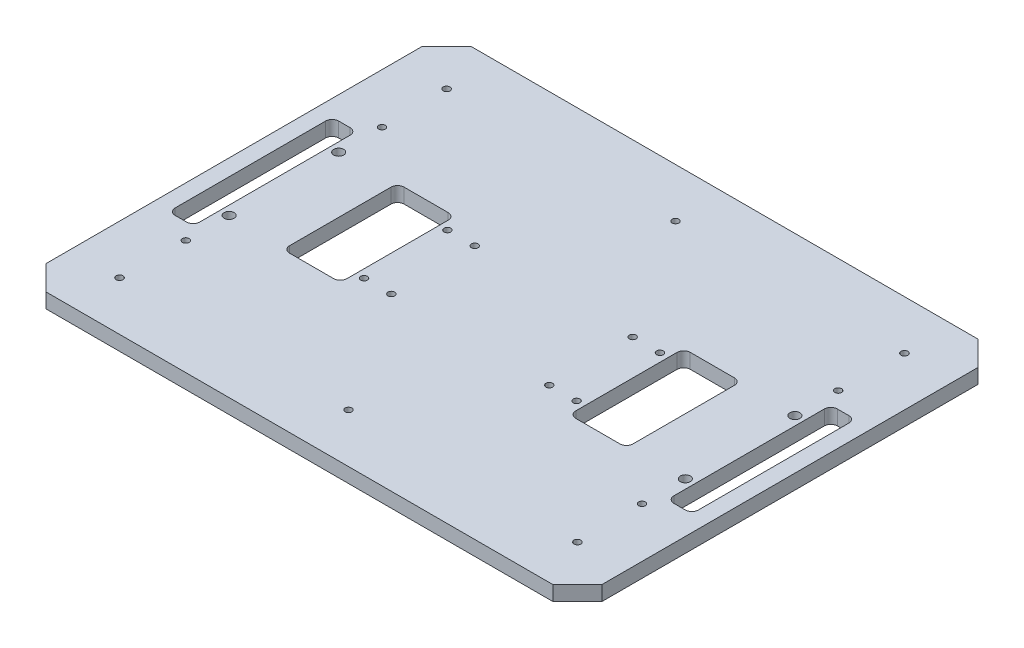
SolidWorks part; units mm, degrees
ref_plane "Plan de face" through (0, 0, 0) normal (0, 0, 1) x (1, 0, 0)
ref_plane "Plan de dessus" through (0, 0, 0) normal (0, 1, 0) x (1, 0, 0)
ref_plane "Plan de droite" through (0, 0, 0) normal (1, 0, 0) x (0, 0, -1)
sketch "Esquisse3" plane through (0, 0, 0) normal (0, 1, 0) x (1, 0, 0)
  line L0 (-281.7629, 0) -> (308.2067, 0) construction
  line L1 (0, 156.6109) -> (0, -136.5502) construction
  line L2 (155, 130) -> (-155, 130)
  line L3 (-170, 115) -> (-170, -115)
  line L4 (-160, -46) -> (-160, 46)
  line L5 (-156, 50) -> (-149, 50)
  line L6 (-145, 46) -> (-145, -46)
  line L7 (-105, 0) -> (-105, 31)
  line L8 (-101, 35) -> (-74, 35)
  line L9 (-70, 31) -> (-70, -31)
  line L10 (-155, 130) -> (-170, 115)
  line L11 (-105, 0) -> (-105, -31)
  line L12 (-101, -35) -> (-74, -35)
  line L13 (-156, -50) -> (-149, -50)
  line L14 (-155, -130) -> (-170, -115)
  line L15 (155, -130) -> (-155, -130)
  line L16 (155, -130) -> (170, -115)
  line L17 (156, 50) -> (149, 50)
  line L18 (156, -50) -> (149, -50)
  line L19 (145, 46) -> (145, -46)
  line L20 (160, -46) -> (160, 46)
  line L21 (105, 0) -> (105, 31)
  line L22 (101, -35) -> (74, -35)
  line L23 (105, 0) -> (105, -31)
  line L24 (70, 31) -> (70, -31)
  line L25 (101, 35) -> (74, 35)
  line L26 (170, 115) -> (170, -115)
  line L27 (155, 130) -> (170, 115)
  arc A0 (-149, 50) -> (-145, 46) centre (-149, 46) cw
  arc A1 (-74, 35) -> (-70, 31) centre (-74, 31) cw
  arc A2 (-105, 31) -> (-101, 35) centre (-101, 31) cw
  arc A3 (-160, 46) -> (-156, 50) centre (-156, 46) cw
  arc A4 (-105, -31) -> (-101, -35) centre (-101, -31) ccw
  arc A5 (-74, -35) -> (-70, -31) centre (-74, -31) ccw
  arc A6 (-160, -46) -> (-156, -50) centre (-156, -46) ccw
  arc A7 (-149, -50) -> (-145, -46) centre (-149, -46) ccw
  arc A8 (149, 50) -> (145, 46) centre (149, 46) ccw
  arc A9 (160, 46) -> (156, 50) centre (156, 46) ccw
  arc A10 (149, -50) -> (145, -46) centre (149, -46) cw
  arc A11 (160, -46) -> (156, -50) centre (156, -46) cw
  arc A12 (74, -35) -> (70, -31) centre (74, -31) cw
  arc A13 (105, -31) -> (101, -35) centre (101, -31) cw
  arc A14 (105, 31) -> (101, 35) centre (101, 31) ccw
  arc A15 (74, 35) -> (70, 31) centre (74, 31) ccw
  circle A16 centre (-140, 100) radius 2.1
  circle A17 centre (-140, -100) radius 2.1
  circle A18 centre (140, -100) radius 2.1
  circle A19 centre (140, 100) radius 2.1
  point P6 (-170, 130)
  point P16 (-105, 15.5)
  point P19 (-145, 50)
  point P22 (-70, 35)
  point P25 (-105, 35)
  point P28 (-160, 50)
  point P32 (-70, 0)
  point P37 (-105, -35)
  point P38 (-70, -35)
  point P40 (-145, 0)
  point P41 (-160, 0)
  point P45 (-160, -50)
  point P46 (-145, -50)
  point P48 (-170, 0)
  point P51 (0, -130)
  point P64 (145, -50)
  point P65 (160, -50)
  point P75 (70, -35)
  point P76 (105, -35)
  point P81 (105, 35)
  point P82 (70, 35)
  point P85 (0, 130)
  dimension "D7" = 4
  dimension "D10" = 4.2
  dimension "D1" = 170
  dimension "D2" = 130
  dimension "D3" = 35
  dimension "D4" = 15
  dimension "D5" = 70
  dimension "D6" = 40
  dimension "D8" = 35
  dimension "D9" = 50
  dimension "D11" = 30
  dimension "D12" = 30
extrude "Boss.-Extru.2" add sketch "Esquisse3" against normal blind 9
sketch "Esquisse4" plane through (0, 0, 0) normal (0, 1, 0) x (1, 0, 0)
  line L0 (-232.6304, 0) -> (230.9735, 0) construction
  line L1 (0, 112.1729) -> (0, -129.4048) construction
  line L2 (-145, -46) -> (-145, 46) construction
  line L3 (-145, -46) -> (-145, 46)
  circle A0 centre (-139.5, 33.5) radius 3.05
  circle A2 centre (-139.5, -33.5) radius 3.05
  circle A3 centre (139.5, -33.5) radius 3.05
  circle A4 centre (139.5, 33.5) radius 3.05
  dimension "D1" = 6.1
  dimension "D3" = 33.5
  dimension "D4" = 5.5
extrude "Enlèv. mat.-Extru.3" cut sketch "Esquisse4" against normal blind 5 contours A3 | A4 | A2 | A0
sketch "Esquisse5" plane through (0, 0, 0) normal (0, 1, 0) x (1, 0, 0)
  line L0 (-244.8916, 0) -> (242.9033, 0) construction
  line L1 (0, 111.8416) -> (0, -134.3756) construction
  line L2 (-145, -46) -> (-145, 46) construction
  line L3 (-145, -46) -> (-145, 46)
  circle A0 centre (-139.5, 60) radius 2.05
  circle A1 centre (-139.5, -60) radius 2.05
  circle A2 centre (139.5, -60) radius 2.05
  circle A3 centre (139.5, 60) radius 2.05
  dimension "D3" = 4.1
  dimension "D1" = 60
  dimension "D2" = 5.5
extrude "Enlèv. mat.-Extru.4" cut sketch "Esquisse5" against normal through all contours A1 | A0 | A3 | A2
sketch "Esquisse6" plane through (0, 0, 0) normal (0, 1, 0) x (1, 0, 0)
  line L0 (0, 109.8533) -> (0, -117.4751) construction
  line L1 (-179.2779, 0) -> (195.847, 0) construction
  line L2 (-98.5767, 25.5) -> (7.2216, 25.5) construction
  line L3 (-70, -31) -> (-70, 31) construction
  circle A0 centre (-65, 25.5) radius 2.05
  circle A1 centre (-48.3, 25.5) radius 2.05
  circle A2 centre (-48.3, -25.5) radius 2.05
  circle A3 centre (-65, -25.5) radius 2.05
  circle A4 centre (65, -25.5) radius 2.05
  circle A5 centre (48.3, -25.5) radius 2.05
  circle A6 centre (48.3, 25.5) radius 2.05
  circle A7 centre (65, 25.5) radius 2.05
  dimension "D1" = 4.1
  dimension "D2" = 4.1
  dimension "D3" = 16.7
  dimension "D4" = 25.5
  dimension "D5" = 5
extrude "Enlèv. mat.-Extru.5" cut sketch "Esquisse6" against normal through all both and the other way through all
sketch "Esquisse7" plane through (0, 0, 0) normal (0, 1, 0) x (1, 0, 0)
  line L2 (0, -145.9077) -> (0, 135.7674) construction
  line L3 (-194.9191, 0) -> (209.9418, 0) construction
  circle A0 centre (0, 100) radius 2.05
  circle A1 centre (0, -100) radius 2.05
  dimension "D1" = 4.1
  dimension "D2" = 100
extrude "Enlèv. mat.-Extru.6" cut sketch "Esquisse7" against normal through all
